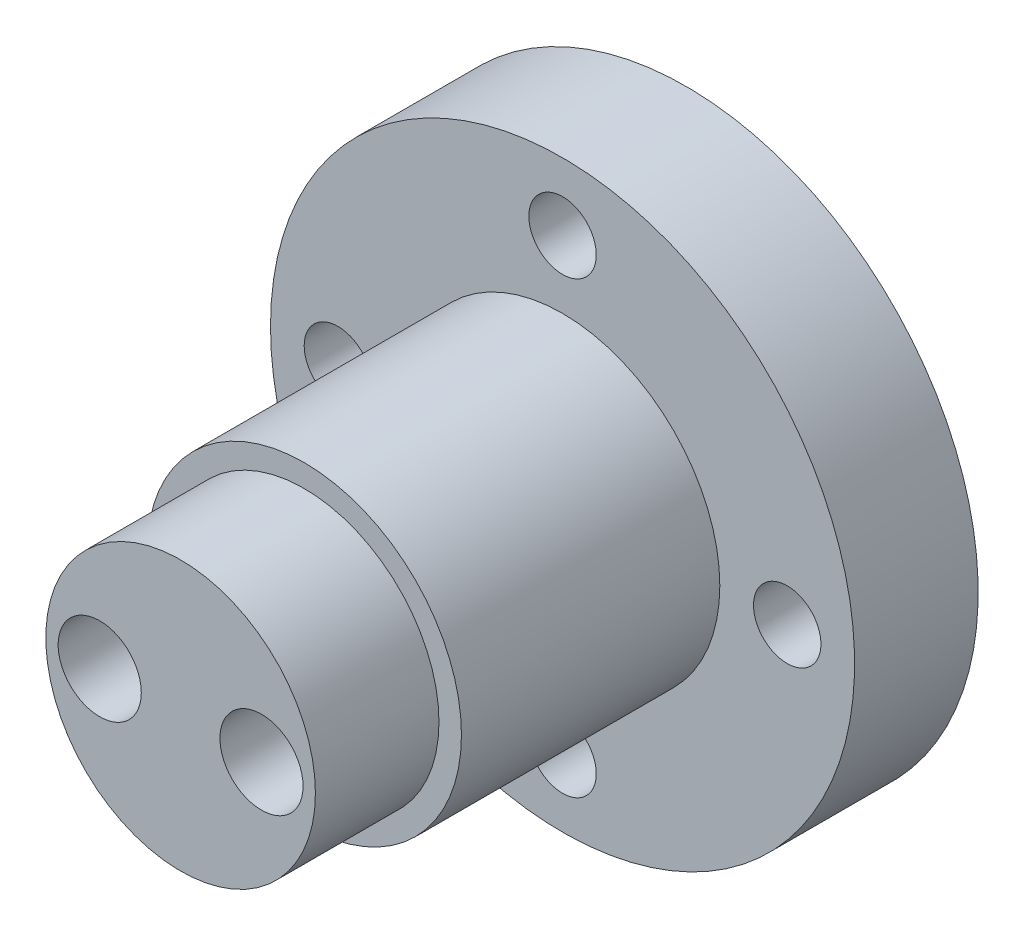
SolidWorks part; units mm, degrees
ref_plane "Front Plane" through (0, 0, 0) normal (0, 0, 1) x (1, 0, 0)
ref_plane "Top Plane" through (0, 0, 0) normal (0, 1, 0) x (1, 0, 0)
ref_plane "Right Plane" through (0, 0, 0) normal (1, 0, 0) x (0, 0, -1)
sketch "Sketch1" plane through (0, 0, 0) normal (0, 0, 1) x (1, 0, 0)
  circle A0 centre (0, 0) radius 7
  dimension "D1" = 14
extrude "Boss-Extrude1" add sketch "Sketch1" along normal blind 11.5
sketch "Sketch2" plane through (0, 0, 11.5) normal (0, 0, 1) x (1, 0, 0)
  circle A0 centre (0, 0) radius 6
  dimension "D1" = 12
extrude "Boss-Extrude2" add sketch "Sketch2" along normal blind 5.5
sketch "Sketch3" plane through (0, 0, 0) normal (0, 0, -1) x (-1, 0, 0)
  circle A0 centre (0, 0) radius 13
  circle A1 centre (0, 0) radius 10 construction
  circle A2 centre (10, 0) radius 1.5
  circle A3 centre (0, -10) radius 1.5
  circle A4 centre (-10, 0) radius 1.5
  circle A5 centre (0, 10) radius 1.5
  point P14 (0, 0)
  dimension "D1" = 26
  dimension "D2" = 20
  dimension "D3" = 3
  dimension "D4" = 4
extrude "Boss-Extrude3" add sketch "Sketch3" along normal blind 5.5
sketch "Sketch4" plane through (0, 0, 17) normal (0, 0, 1) x (1, 0, 0)
  circle A1 centre (0, 0) radius 3.6 construction
  circle A2 centre (3.6, 0) radius 1.85
  circle A3 centre (-3.6, 0) radius 1.85
  circle A5 centre (-3.6, 0) radius 3.5 construction
  circle A6 centre (3.5945, -0.1997) radius 3.5 construction
  point P11 (0, 0)
  dimension "D1" = 3.7
  dimension "D2" = 7.2
  dimension "D4" = 7
  dimension "D5" = 7
  dimension "D3" = 2
extrude "Cut-Extrude1" cut sketch "Sketch4" against normal through all
